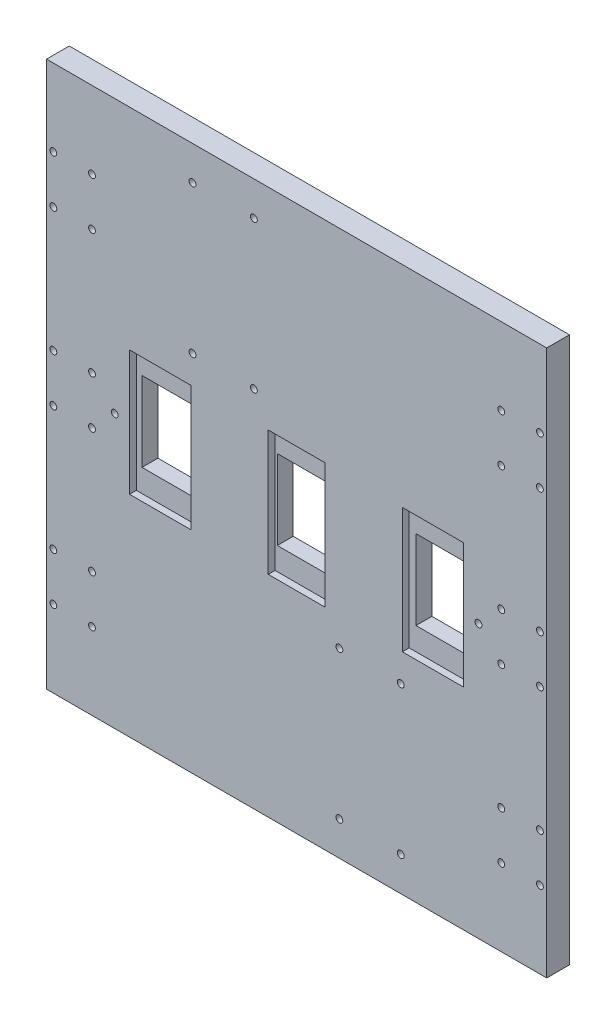
SolidWorks part; units mm, degrees
ref_plane "Front Plane" through (0, 0, 0) normal (0, 0, 1) x (1, 0, 0)
ref_plane "Top Plane" through (0, 0, 0) normal (0, 1, 0) x (1, 0, 0)
ref_plane "Right Plane" through (0, 0, 0) normal (1, 0, 0) x (0, 0, -1)
sketch "Sketch1" plane through (0, 0, 0) normal (0, 0, 1) x (1, 0, 0)
  line L0 (-49.5, 17.5) -> (-49.5, -17.5)
  line L1 (-110, -120) -> (110, -120)
  line L2 (-110, -120) -> (-110, 120)
  line L3 (-110, 120) -> (110, 120)
  line L4 (110, -120) -> (110, 120)
  line L5 (-110, -120) -> (110, 120) construction
  line L6 (-110, 120) -> (110, -120) construction
  line L7 (-68.5, -17.5) -> (-49.5, -17.5)
  line L8 (-68.5, -17.5) -> (-68.5, 17.5)
  line L9 (-68.5, 17.5) -> (-49.5, 17.5)
  line L10 (68.5, -17.5) -> (68.5, 17.5)
  line L11 (-68.5, -17.5) -> (68.5, 17.5) construction
  line L12 (-68.5, 17.5) -> (68.5, -17.5) construction
  line L14 (-9.5, -17.5) -> (-9.5, 17.5)
  line L15 (9.5, 17.5) -> (9.5, -17.5)
  line L16 (49.5, 17.5) -> (49.5, -17.5)
  line L17 (49.5, 17.5) -> (68.5, 17.5)
  line L18 (49.5, -17.5) -> (68.5, -17.5)
  line L19 (-9.5, -17.5) -> (9.5, -17.5)
  line L20 (-9.5, 17.5) -> (9.5, 17.5)
  line L23 (45.8, -40) -> (18.8, -40) construction
  line L24 (-80, 0) -> (80, 0) construction
  line L27 (107, 65.1699) -> (90, 65.1699) construction
  line L28 (107, 65.1699) -> (107, 86.1699) construction
  line L29 (107, 86.1699) -> (90, 86.1699) construction
  line L30 (90, 65.1699) -> (90, 86.1699) construction
  line L31 (107, 65.1699) -> (90, 86.1699) construction
  line L32 (107, 86.1699) -> (90, 65.1699) construction
  line L33 (107, -10.5) -> (90, -10.5) construction
  line L34 (107, -10.5) -> (107, 10.5) construction
  line L35 (107, 10.5) -> (90, 10.5) construction
  line L36 (90, -10.5) -> (90, 10.5) construction
  line L37 (107, -10.5) -> (90, 10.5) construction
  line L38 (107, 10.5) -> (90, -10.5) construction
  line L40 (107, -86.1699) -> (90, -86.1699) construction
  line L41 (107, -86.1699) -> (107, -65.1699) construction
  line L42 (107, -65.1699) -> (90, -65.1699) construction
  line L43 (90, -86.1699) -> (90, -65.1699) construction
  line L44 (107, -86.1699) -> (90, -65.1699) construction
  line L45 (107, -65.1699) -> (90, -86.1699) construction
  line L48 (-90, 65.1699) -> (-107, 65.1699) construction
  line L49 (-90, 65.1699) -> (-90, 86.1699) construction
  line L50 (-90, 86.1699) -> (-107, 86.1699) construction
  line L51 (-107, 65.1699) -> (-107, 86.1699) construction
  line L52 (-90, 65.1699) -> (-107, 86.1699) construction
  line L53 (-90, 86.1699) -> (-107, 65.1699) construction
  line L54 (-90, -10.5) -> (-107, -10.5) construction
  line L55 (-90, -10.5) -> (-90, 10.5) construction
  line L56 (-90, 10.5) -> (-107, 10.5) construction
  line L57 (-107, -10.5) -> (-107, 10.5) construction
  line L58 (-90, -10.5) -> (-107, 10.5) construction
  line L59 (-90, 10.5) -> (-107, -10.5) construction
  line L61 (-90, -86.1699) -> (-107, -86.1699) construction
  line L62 (-90, -86.1699) -> (-90, -65.1699) construction
  line L63 (-90, -65.1699) -> (-107, -65.1699) construction
  line L64 (-107, -86.1699) -> (-107, -65.1699) construction
  line L65 (-90, -86.1699) -> (-107, -65.1699) construction
  line L66 (-90, -65.1699) -> (-107, -86.1699) construction
  circle A12 centre (18.8, -40) radius 1.5
  circle A13 centre (45.8, -40) radius 1.5
  circle A14 centre (45.8, -105) radius 1.5
  circle A15 centre (18.8, -105) radius 1.5
  circle A16 centre (-45.8, 105) radius 1.5
  circle A17 centre (-18.8, 105) radius 1.5
  circle A18 centre (-18.8, 40) radius 1.5
  circle A19 centre (-45.8, 40) radius 1.5
  circle A20 centre (-80, 0) radius 1.5
  circle A21 centre (80, 0) radius 1.5
  circle A22 centre (90, 86.1699) radius 1.5
  circle A23 centre (90, 65.1699) radius 1.5
  circle A24 centre (107, 65.1699) radius 1.5
  circle A25 centre (107, 86.1699) radius 1.5
  circle A26 centre (90, -10.5) radius 1.5
  circle A27 centre (90, 10.5) radius 1.5
  circle A28 centre (107, 10.5) radius 1.5
  circle A29 centre (107, -10.5) radius 1.5
  circle A30 centre (90, -86.1699) radius 1.5
  circle A31 centre (90, -65.1699) radius 1.5
  circle A32 centre (107, -65.1699) radius 1.5
  circle A33 centre (107, -86.1699) radius 1.5
  circle A34 centre (-107, -65.1699) radius 1.5
  circle A35 centre (-107, -86.1699) radius 1.5
  circle A36 centre (-90, -86.1699) radius 1.5
  circle A37 centre (-90, -65.1699) radius 1.5
  circle A38 centre (-107, -10.5) radius 1.5
  circle A39 centre (-107, 10.5) radius 1.5
  circle A40 centre (-90, 10.5) radius 1.5
  circle A41 centre (-90, -10.5) radius 1.5
  circle A42 centre (-107, 86.1699) radius 1.5
  circle A43 centre (-107, 65.1699) radius 1.5
  circle A44 centre (-90, 65.1699) radius 1.5
  circle A45 centre (-90, 86.1699) radius 1.5
  point P0 (0, 0)
  point P6 (0, 0)
  point P47 (98.5, 0)
  point P68 (0, 0)
  point P69 (98.5, 75.6699)
  point P78 (98.5, -75.6699)
  point P95 (-98.5, 75.6699)
  point P100 (-98.5, 0)
  point P105 (-98.5, -75.6699)
  dimension "D11" = 3
  dimension "D16" = 3
  dimension "D22" = 3
  dimension "D30" = 3
  dimension "D32" = 3
  dimension "D33" = 3
  dimension "D36" = 3
  dimension "D1" = 220
  dimension "D2" = 240
  dimension "D4" = 35
  dimension "D5" = 40
  dimension "D6" = 40
  dimension "D7" = 19
  dimension "D12" = 27
  dimension "D13" = 65
  dimension "D14" = 15
  dimension "D15" = 64.2
  dimension "D17" = 65
  dimension "D18" = 27
  dimension "D19" = 64.2
  dimension "D20" = 15
  dimension "D21" = 3
  dimension "D23" = 160
  dimension "D24" = 21
  dimension "D25" = 17
  dimension "D26" = 21
  dimension "D27" = 17
  dimension "D28" = 21
  dimension "D29" = 17
  dimension "D31" = 33.8301
  dimension "D34" = 21
  dimension "D35" = 17
  dimension "D37" = 33.8301
  dimension "D38" = 3
extrude "Boss-Extrude1" add sketch "Sketch1" along normal blind 10
sketch "Sketch2" plane through (0, 0, 10) normal (0, 0, 1) x (1, 0, 0)
  line L0 (-68.5, 17.5) -> (-68.5, -17.5) construction
  line L1 (-73.5, -27.5) -> (73.5, -27.5)
  line L2 (-73.5, -27.5) -> (-73.5, 27.5)
  line L3 (-73.5, 27.5) -> (73.5, 27.5)
  line L4 (73.5, -27.5) -> (73.5, 27.5)
  line L5 (-73.5, -27.5) -> (73.5, 27.5) construction
  line L6 (-73.5, 27.5) -> (73.5, -27.5) construction
  line L7 (-49.5, 17.5) -> (-68.5, 17.5) construction
  point P0 (0, 0)
  dimension "D1" = 5
  dimension "D2" = 10
extrude "Cut-Extrude1" cut sketch "Sketch2" against normal blind 3 and the other way through all
sketch "Sketch3" plane through (0, 0, 7) normal (0, 0, 1) x (1, 0, 0)
  line L0 (73.5, 27.5) -> (-73.5, 27.5) construction
  line L1 (46.5, 27.5) -> (12.5, 27.5)
  line L2 (46.5, 27.5) -> (46.5, -27.5)
  line L3 (46.5, -27.5) -> (12.5, -27.5)
  line L4 (12.5, 27.5) -> (12.5, -27.5)
  line L5 (-73.5, -27.5) -> (73.5, -27.5) construction
  line L7 (-12.5, 27.5) -> (-46.5, 27.5)
  line L8 (-12.5, 27.5) -> (-12.5, -27.5)
  line L9 (-12.5, -27.5) -> (-46.5, -27.5)
  line L10 (-46.5, 27.5) -> (-46.5, -27.5)
  line L11 (-49.5, 17.5) -> (-49.5, -17.5) construction
  line L12 (-9.5, -17.5) -> (-9.5, 17.5) construction
  line L13 (9.5, 17.5) -> (9.5, -17.5) construction
  dimension "D1" = 3
  dimension "D2" = 3
  dimension "D3" = 3
extrude "Boss-Extrude2" add sketch "Sketch3" along normal up to surface (3 mm away) up to face at (-88.5, 86.1699, 10)
ref_plane "Plane1" through (-49.5, 17.5, 0) normal (0, 1, 0) x (1, 0, 0)
sketch "Sketch6" plane through (0, 0, 7) normal (0, 0, 1) x (1, 0, 0)
  line L0 (68.5, 17.5) -> (68.5, -17.5) construction
  line L1 (-68.5, 17.5) -> (-71, 17.5)
  line L2 (-68.5, 17.5) -> (-68.5, -17.5)
  line L3 (-68.5, -17.5) -> (-71, -17.5)
  line L4 (-71, 17.5) -> (-71, -17.5)
  line L5 (68.5, 17.5) -> (71, 17.5)
  line L6 (68.5, 17.5) -> (68.5, -17.5)
  line L7 (68.5, -17.5) -> (71, -17.5)
  line L8 (71, 17.5) -> (71, -17.5)
  line L9 (68.5, -17.5) -> (49.5, -17.5) construction
  line L10 (-49.5, -17.5) -> (-68.5, -17.5) construction
  line L11 (49.5, 17.5) -> (68.5, 17.5) construction
  dimension "D1" = 2.5
  dimension "D2" = 2.5
extrude "Cut-Extrude3" cut sketch "Sketch6" against normal blind 10
sketch "Sketch7" plane through (0, 0, 7) normal (0, 0, 1) x (1, 0, 0)
  line L0 (9.5, -17.5) -> (-9.5, -17.5) construction
  line L1 (9.5, 17.5) -> (11.5, 17.5)
  line L2 (9.5, 17.5) -> (9.5, -17.5)
  line L3 (9.5, -17.5) -> (11.5, -17.5)
  line L4 (11.5, 17.5) -> (11.5, -17.5)
  line L5 (-9.5, 17.5) -> (-11.5, 17.5)
  line L6 (-9.5, 17.5) -> (-9.5, -17.5)
  line L7 (-9.5, -17.5) -> (-11.5, -17.5)
  line L8 (-11.5, 17.5) -> (-11.5, -17.5)
  dimension "D1" = 2
  dimension "D2" = 2
extrude "Cut-Extrude4" cut sketch "Sketch7" against normal blind 10
